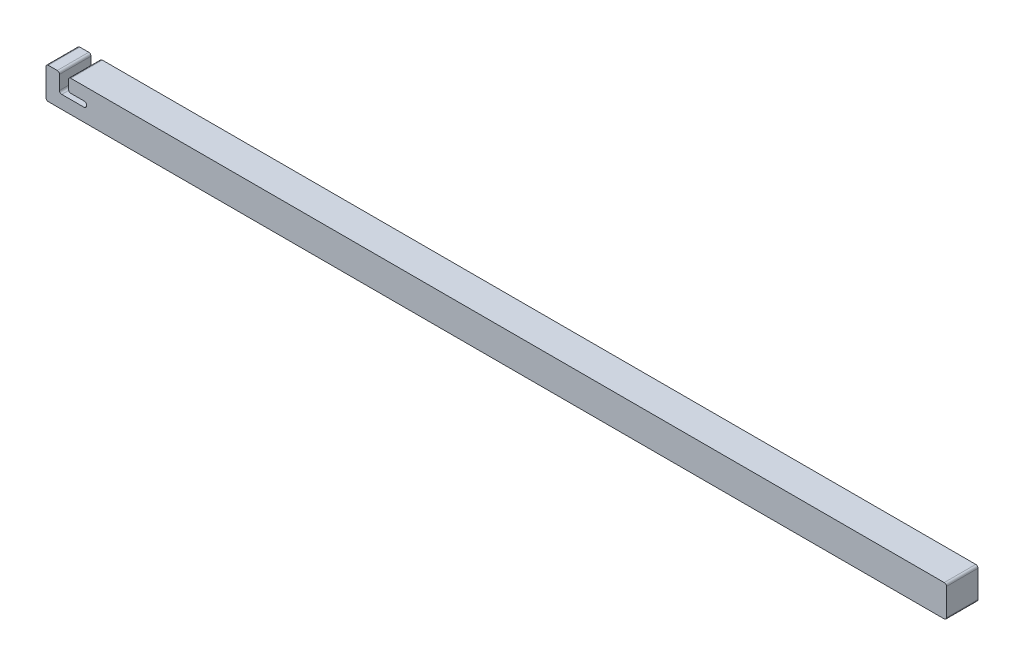
SolidWorks part; units mm, degrees
ref_plane "Front Plane" through (0, 0, 0) normal (0, 0, 1) x (1, 0, 0)
ref_plane "Top Plane" through (0, 0, 0) normal (0, 1, 0) x (1, 0, 0)
ref_plane "Right Plane" through (0, 0, 0) normal (1, 0, 0) x (0, 0, -1)
sketch "Sketch1" plane through (0, 0, 0) normal (0, 0, 1) x (1, 0, 0)
  line L1 (-100, 3.5) -> (100, 3.5)
  line L2 (-100, 3.5) -> (-100, -3.5)
  line L3 (-100, -3.5) -> (100, -3.5)
  line L4 (100, 3.5) -> (100, -3.5)
  line L5 (-100, 3.5) -> (100, -3.5) construction
  line L6 (-100, -3.5) -> (100, 3.5) construction
  point P0 (0, 0)
  dimension "D1" = 200
  dimension "D2" = 7
extrude "Boss-Extrude1" add sketch "Sketch1" along normal blind 7
sketch "Sketch2" plane through (0, -3.5, 7) normal (0, 0, -1) x (1, 0, 0)
  line L0 (-97, -7) -> (-97, -2.9)
  line L1 (-97, -2.9) -> (-91, -2.9)
  line L2 (-91, -2.9) -> (-91, -4.1)
  line L3 (-91, -4.1) -> (-95, -4.1)
  line L4 (-95, -4.1) -> (-95, -7)
  line L5 (-95, -7) -> (-97, -7)
  line L6 (100, -7) -> (-100, -7) construction
  line L8 (-100, -7) -> (-100, 0) construction
  point P8 (-91, -3.5)
  point P11 (-100, -3.5)
  dimension "D1" = 1.2
  dimension "D2" = 3
  dimension "D3" = 6
  dimension "D4" = 2
extrude "Cut-Extrude2" cut sketch "Sketch2" along normal through all
fillet "Fillet1" radius 0.5 10 edges at (100, -3.5, 3.5) (100, 3.5, 3.5) (-100, -3.5, 3.5) (-95, 0.6, 3.5) (-91, 0.6, 3.5) (-91, -0.6, 3.5) (-97, -0.6, 3.5) (-95, 3.5, 3.5) (-97, 3.5, 3.5) (-100, 3.5, 3.5)
